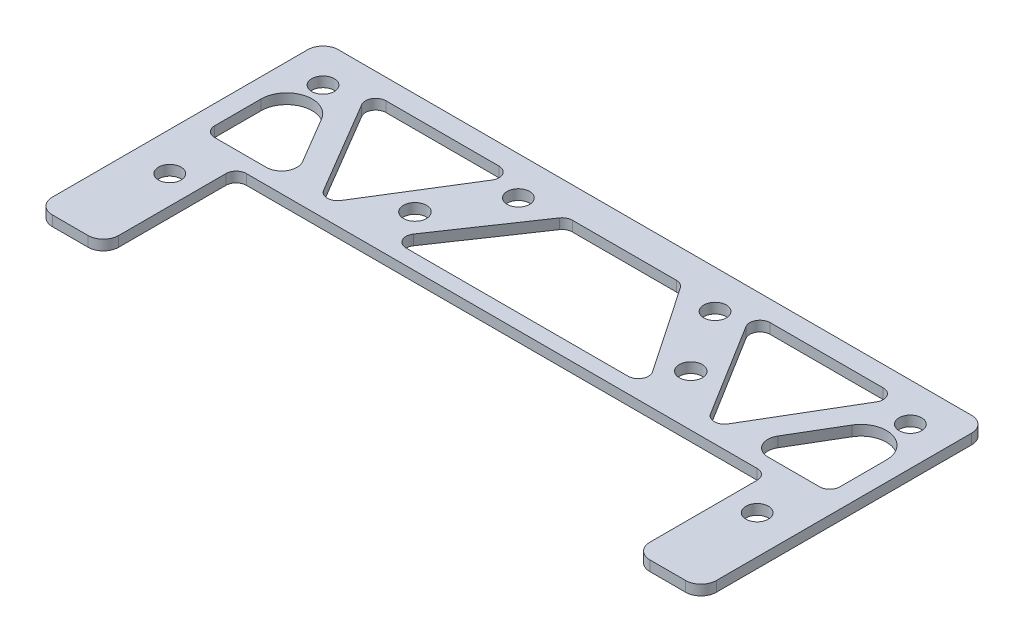
SolidWorks part; units mm, degrees
ref_plane "前视基准面" through (0, 0, 0) normal (0, 0, 1) x (1, 0, 0)
ref_plane "上视基准面" through (0, 0, 0) normal (0, 1, 0) x (1, 0, 0)
ref_plane "右视基准面" through (0, 0, 0) normal (1, 0, 0) x (0, 0, -1)
other "Configuration Table"
sketch "草图1" plane through (0, 0, 0) normal (0, 1, 0) x (1, 0, 0)
  line L0 (13, 0) -> (13, -56)
  line L1 (0, 0) -> (130, 0)
  line L2 (0, 0) -> (0, -56)
  line L3 (0, -56) -> (130, -56)
  line L4 (130, 0) -> (130, -56)
  line L5 (117, 0) -> (117, -56)
  line L6 (65, 0) -> (65, -56) construction
  line L7 (0, -15) -> (130, -15)
  line L8 (0, -7.5) -> (130, -7.5) construction
  line L9 (7.5, 0) -> (7.5, -56) construction
  line L10 (122.5, 0) -> (122.5, -56) construction
  line L11 (0, -34) -> (130, -34)
  circle A0 centre (7.5, -7.5) radius 2.2
  circle A1 centre (7.5, -37.5) radius 2.2
  circle A2 centre (45.75, -7.5) radius 2.2
  circle A3 centre (84.25, -7.5) radius 2.2
  circle A4 centre (122.5, -37.5) radius 2.2
  circle A5 centre (122.5, -7.5) radius 2.2
  dimension "D9" = 30
  dimension "D10" = 4.4
  dimension "D11" = 38.5
  dimension "D1" = 130
  dimension "D2" = 56
  dimension "D3" = 13
  dimension "D4" = 15
  dimension "D5" = 7.5
  dimension "D6" = 7.5
  dimension "D7" = 7.5
  dimension "D8" = 34
extrude "凸台-拉伸3" add sketch "草图1" along normal blind 2 contours L11 L2 L3 L0 A1 | L2 L11 L0 L7 | L2 L7 L0 L1 A0 | L0 L7 L5 L1 A3 A2 | L5 L7 L4 L1 A5 | L5 L11 L4 L7 | L11 L5 L3 L4 A4 | L0 L11 L5 L7
sketch "草图2" plane through (0, 2, 0) normal (0, 1, 0) x (1, 0, 0)
  line L0 (65, 0) -> (65, -34) construction
  line L1 (0, -20) -> (130, -20) construction
  line L8 (130, 0) -> (0, 0)
  line L9 (0, 0) -> (0, -56)
  line L10 (0, -56) -> (13, -56)
  line L11 (13, -56) -> (13, -34)
  line L12 (13, -34) -> (117, -34)
  line L13 (117, -34) -> (117, -56)
  line L14 (0, -56) -> (13, -56)
  line L15 (130, -56) -> (130, 0)
  line L16 (130, 0) -> (0, 0)
  line L17 (0, 0) -> (0, -56)
  line L19 (13, -56) -> (13, -34)
  line L20 (13, -34) -> (117, -34)
  line L21 (117, -34) -> (117, -56)
  line L23 (130, -56) -> (130, 0)
  line L26 (117, -56) -> (130, -56)
  line L27 (117, -56) -> (130, -56)
  circle A0 centre (38, -20) radius 2.25
  circle A1 centre (92, -20) radius 2.25
  dimension "D3" = 4.5
  dimension "D4" = 54
  dimension "D2" = 20
  dimension "D1" = 0
extrude "切除-拉伸1" cut sketch "草图2" against normal blind 10 contours A0 | A1
sketch "草图3" plane through (0, 2, 0) normal (0, 1, 0) x (1, 0, 0)
  line L0 (16.3202, -4) -> (38.4438, -4)
  line L1 (40.1436, -7.0539) -> (28.8171, -25.3223)
  line L2 (25.3956, -25.2861) -> (14.5984, -7.0176)
  line L3 (45.75, -7.5) -> (38, -20)
  line L4 (18.4779, -22.4736) -> (13.0932, -13.3627)
  line L5 (3.7887, -15.9067) -> (3.7887, -25)
  line L6 (5.7887, -27) -> (15.8953, -27)
  line L7 (65, 0) -> (65, -34) construction
  line L8 (130, 0) -> (0, 0)
  line L9 (0, 0) -> (0, -56)
  line L10 (0, -56) -> (13, -56)
  line L11 (13, -56) -> (13, -34)
  line L12 (13, -34) -> (117, -34)
  line L13 (117, -34) -> (117, -56)
  line L14 (0, -56) -> (13, -56)
  line L15 (130, -56) -> (130, 0)
  line L16 (130, 0) -> (0, 0)
  line L17 (0, 0) -> (0, -56)
  line L19 (13, -56) -> (13, -34)
  line L20 (13, -34) -> (117, -34)
  line L21 (117, -34) -> (117, -56)
  line L23 (130, -56) -> (130, 0)
  line L24 (126.2113, -15.9067) -> (126.2113, -25)
  line L25 (111.5221, -22.4736) -> (116.9068, -13.3627)
  line L26 (124.2113, -27) -> (114.1047, -27)
  line L27 (89.8564, -7.0539) -> (101.1829, -25.3223)
  line L28 (113.6798, -4) -> (91.5562, -4)
  line L29 (104.6044, -25.2861) -> (115.4016, -7.0176)
  line L30 (54.8098, -6) -> (75.1902, -6)
  line L31 (76.8451, -6.877) -> (88.3808, -23.877)
  line L32 (86.7259, -27) -> (43.2741, -27)
  line L33 (41.6192, -23.877) -> (53.1549, -6.877)
  line L42 (117, -56) -> (130, -56)
  line L43 (117, -56) -> (130, -56)
  circle A0 centre (7.5, -7.5) radius 2.2 construction
  circle A1 centre (7.5, -7.5) radius 2.2
  circle A2 centre (122.5, -7.5) radius 2.2 construction
  circle A3 centre (92, -20) radius 2.25 construction
  circle A4 centre (84.25, -7.5) radius 2.2 construction
  circle A5 centre (38, -20) radius 2.25 construction
  circle A6 centre (45.75, -7.5) radius 2.2 construction
  circle A7 centre (122.5, -7.5) radius 2.2
  circle A24 centre (92, -20) radius 2.25
  circle A25 centre (84.25, -7.5) radius 2.2
  circle A26 centre (38, -20) radius 2.25
  circle A27 centre (45.75, -7.5) radius 2.2
  arc A28 (13.0932, -13.3627) -> (3.7887, -15.9067) centre (8.7887, -15.9067) ccw
  arc A29 (18.4779, -22.4736) -> (15.8953, -27) centre (15.8953, -24) cw
  arc A30 (3.7887, -25) -> (5.7887, -27) centre (5.7887, -25) ccw
  arc A31 (16.3202, -4) -> (14.5984, -7.0176) centre (16.3202, -6) ccw
  arc A32 (28.8171, -25.3223) -> (25.3956, -25.2861) centre (27.1173, -24.2684) cw
  arc A33 (38.4438, -4) -> (40.1436, -7.0539) centre (38.4438, -6) cw
  arc A34 (116.9068, -13.3627) -> (126.2113, -15.9067) centre (121.2113, -15.9067) cw
  arc A35 (111.5221, -22.4736) -> (114.1047, -27) centre (114.1047, -24) ccw
  arc A36 (126.2113, -25) -> (124.2113, -27) centre (124.2113, -25) cw
  arc A37 (91.5562, -4) -> (89.8564, -7.0539) centre (91.5562, -6) ccw
  arc A38 (113.6798, -4) -> (115.4016, -7.0176) centre (113.6798, -6) cw
  arc A39 (101.1829, -25.3223) -> (104.6044, -25.2861) centre (102.8827, -24.2684) ccw
  arc A40 (75.1902, -6) -> (76.8451, -6.877) centre (75.1902, -8) cw
  arc A41 (88.3808, -23.877) -> (86.7259, -27) centre (86.7259, -25) cw
  arc A42 (43.2741, -27) -> (41.6192, -23.877) centre (43.2741, -25) cw
  arc A43 (54.8098, -6) -> (53.1549, -6.877) centre (54.8098, -8) ccw
  point P89 (76.25, -6)
  point P92 (90.5, -27)
  point P95 (39.5, -27)
  point P98 (53.75, -6)
  dimension "D5" = 5
  dimension "D6" = 3
  dimension "D7" = 2
  dimension "D8" = 2
  dimension "D9" = 2
  dimension "D10" = 2
  dimension "D14" = 2
  dimension "D2" = 5
  dimension "D3" = 4
  dimension "D4" = 7
  dimension "D11" = 7
  dimension "D12" = 22.5
  dimension "D13" = 51
  dimension "D1" = 0
extrude "切除-拉伸2" cut sketch "草图3" against normal blind 10 contours A33 L0 A31 L2 A32 L1 | L5 A30 L6 A29 L4 A28 | L7 L30 A43 L33 A42 L32 | L30 L7 L32 A41 L31 A40 | L27 A39 L29 A38 L28 A37 | A36 L24 A34 L25 A35 L26
sketch "草图4" plane through (0, 2, 0) normal (0, 1, 0) x (1, 0, 0)
  line L0 (13, -34) -> (117, -34) construction
  line L1 (13, -34) -> (117, -34)
  line L2 (13, -34) -> (13, -30)
  line L3 (13, -30) -> (117, -30)
  line L4 (117, -30) -> (117, -34)
  dimension "D1" = 4
extrude "切除-拉伸3" cut sketch "草图4" against normal blind 10
fillet "圆角1" radius 2 2 edges at (117, 1, 30) (13, 1, 30)
fillet "圆角2" radius 3 6 edges at (0, 1, 0) (130, 1, 0) (117, 1, 56) (130, 1, 56) (0, 1, 56) (13, 1, 56)
